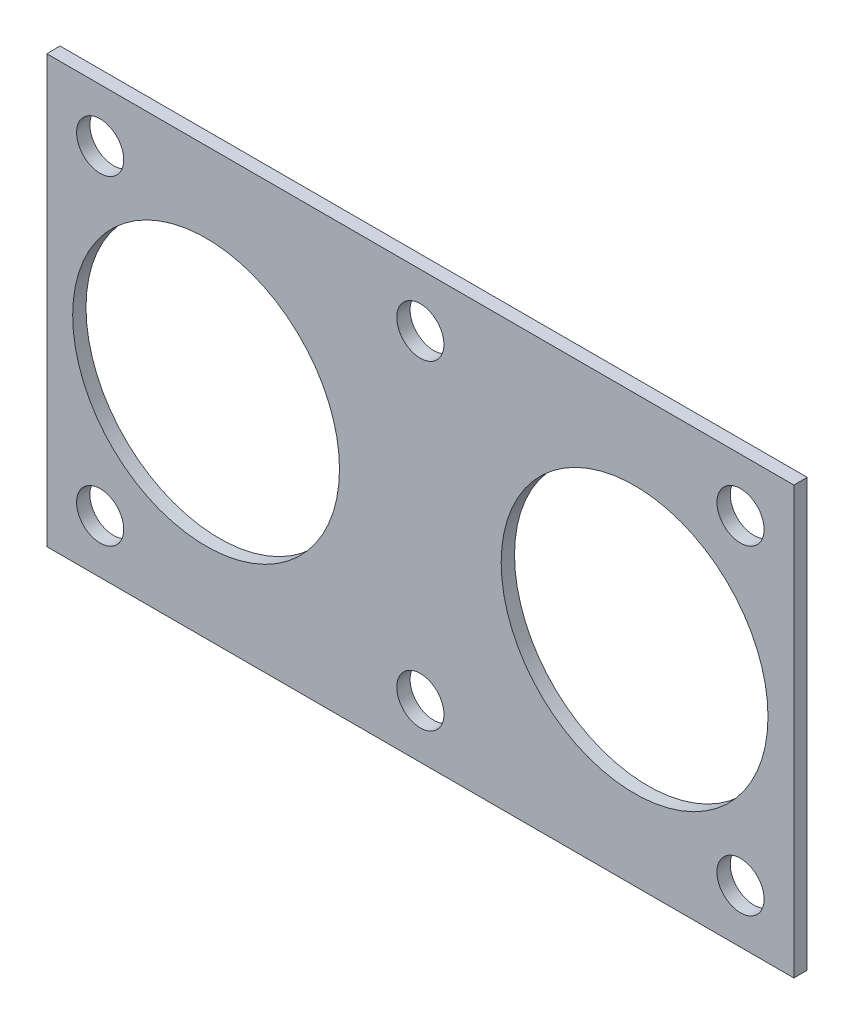
SolidWorks part; units mm, degrees
material "ABS PC"
ref_plane "Front Plane" through (0, 0, 0) normal (0, 0, 1) x (1, 0, 0)
ref_plane "Top Plane" through (0, 0, 0) normal (0, 1, 0) x (1, 0, 0)
ref_plane "Right Plane" through (0, 0, 0) normal (1, 0, 0) x (0, 0, -1)
sketch "Sketch1" plane through (0, 0, 0) normal (0, 0, 1) x (1, 0, 0)
  line L1 (-18.9548, 25.4) -> (69.9452, 25.4)
  line L2 (-18.9548, 25.4) -> (-18.9547, -25.4)
  line L3 (-18.9547, -25.4) -> (69.9452, -25.4)
  line L4 (69.9452, 25.4) -> (69.9452, -25.4)
  circle A0 centre (0, 0) radius 15.875
  circle A1 centre (50.9905, 0) radius 15.875
  circle A2 centre (0, 0) radius 15.875 construction
  circle A3 centre (50.9905, 0) radius 15.875 construction
extrude "Boss-Extrude1" add sketch "Sketch1" along normal up to surface (1.5875 mm away)
hole_wizard "#10 Clearance Hole1" positions "Sketch2" profile "Sketch3" hole size "#10" standard "ANSI Inch" end condition through all
sketch "Sketch2" plane through (-41.275, -44.45, 1.5875) normal (0, 0, 1) x (1, 0, 0)
  line L16 (28.6702, 63.5) -> (28.6702, 25.4)
  line L17 (28.6702, 25.4) -> (104.8702, 25.4)
  line L18 (104.8702, 25.4) -> (104.8702, 63.5)
  line L19 (104.8702, 63.5) -> (28.6702, 63.5)
  point P0 (104.8702, 63.5)
  point P2 (28.6702, 63.5)
  point P4 (66.7702, 25.4)
  point P6 (28.6702, 25.4)
  point P8 (66.7702, 63.5)
  point P10 (104.8702, 25.4)
  point P22 (0, 0)
  point P51 (24.8602, 67.31)
  point P52 (66.7702, 67.31)
  point P53 (108.6802, 67.31)
  point P54 (108.6802, 21.59)
  point P55 (66.7702, 21.59)
  point P56 (24.8602, 21.59)
sketch "Sketch3" plane through (63.5952, 19.05, 1.5875) normal (1, 0, 0) x (0, -1, 0)
  line L0 (0, 0) -> (0, 1.5875)
  line L1 (0, 1.5875) -> (2.8067, 1.5875)
  line L2 (2.8067, 1.5875) -> (2.8067, 0)
  line L5 (2.8067, 0) -> (0, 0)
  line L11 (0, -6.35) -> (0, 107.95) construction
  dimension "Thru Hole Dia." = 5.6134
  dimension "Thru Hole Depth" = 1.5875
